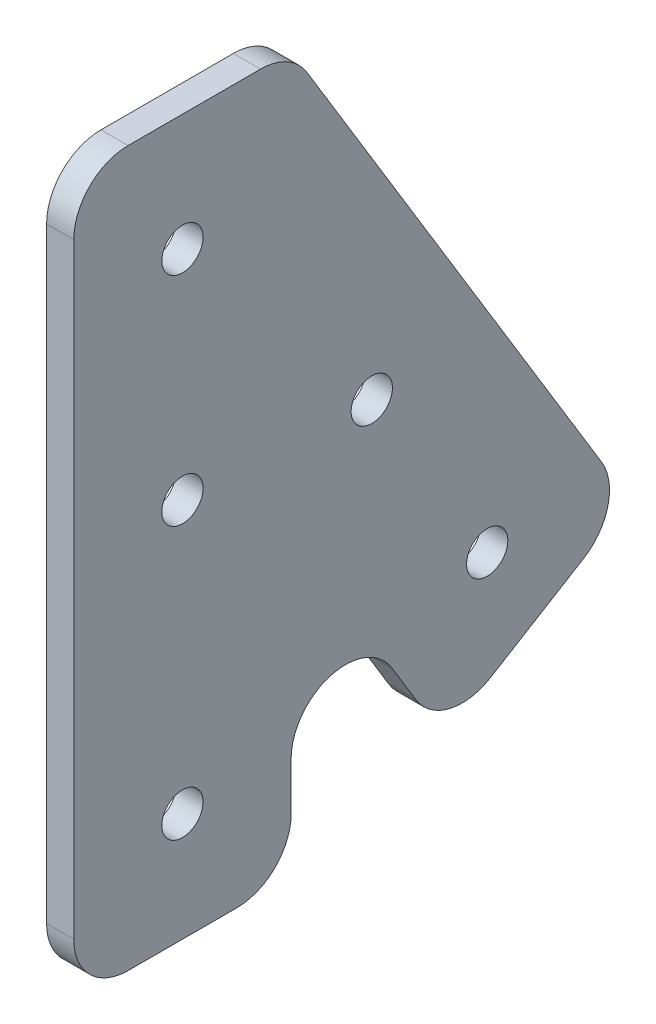
SolidWorks part; units mm, degrees
ref_plane "Front Plane" through (0, 0, 0) normal (0, 0, 1) x (1, 0, 0)
ref_plane "Top Plane" through (0, 0, 0) normal (0, 1, 0) x (1, 0, 0)
ref_plane "Right Plane" through (0, 0, 0) normal (1, 0, 0) x (0, 0, -1)
sketch "Sketch1" plane through (0, 0, 0) normal (1, 0, 0) x (0, 0, -1)
  line L0 (27.2549, 80.4378) -> (61.678, 23.7995)
  line L1 (6.35, 0) -> (19.05, 0)
  line L2 (0, 6.35) -> (0, 77.1398)
  line L3 (6.35, 83.4898) -> (21.8285, 83.4898)
  line L4 (25.4, 6.35) -> (25.4, 11.91)
  line L5 (59.5496, 15.0751) -> (48.6968, 8.4791)
  line L6 (39.9724, 10.6075) -> (37.1764, 15.208)
  arc A0 (39.9724, 10.6075) -> (48.6968, 8.4791) centre (45.3988, 13.9055) ccw
  arc A1 (59.5496, 15.0751) -> (61.678, 23.7995) centre (56.2516, 20.5015) ccw
  arc A2 (27.2549, 80.4378) -> (21.8285, 83.4898) centre (21.8285, 77.1398) ccw
  arc A3 (6.35, 83.4898) -> (0, 77.1398) centre (6.35, 77.1398) ccw
  arc A4 (6.35, 0) -> (0, 6.35) centre (6.35, 6.35) cw
  arc A5 (19.05, 0) -> (25.4, 6.35) centre (19.05, 6.35) ccw
  arc A6 (37.1764, 15.208) -> (25.4, 11.91) centre (31.75, 11.91) ccw
  point P10 (43.2704, 5.1811)
  point P13 (64.976, 18.3731)
  point P16 (25.4, 83.4898)
  point P19 (0, 83.4898)
  point P22 (0, 0)
  dimension "D7" = 6.35
  dimension "D1" = 25.4
  dimension "D2" = 83.4898
  dimension "D3" = 76.2
  dimension "D4" = 121.29
  dimension "D5" = 25.4
  dimension "D6" = 90
extrude "Boss-Extrude1" add sketch "Sketch1" along normal blind 3.175
sketch "Sketch2" plane through (3.175, 0, 0) normal (1, 0, 0) x (0, 0, -1)
  line L0 (6.35, 0) -> (19.05, 0) construction
  line L1 (61.678, 23.7995) -> (27.2549, 80.4378) construction
  circle A0 centre (12.7, 12.7) radius 2.413
  circle A1 centre (12.7, 44.45) radius 2.413
  circle A2 centre (12.7, 69.85) radius 2.413
  circle A3 centre (34.8216, 43.5352) radius 2.413
  circle A4 centre (48.3095, 21.3428) radius 2.413
  dimension "D1" = 4.826
  dimension "D2" = 12.7
  dimension "D3" = 4.826
  dimension "D4" = 31.75
  dimension "D5" = 4.826
  dimension "D6" = 25.4
  dimension "D7" = 4.826
  dimension "D8" = 12.7
  dimension "D9" = 4.826
  dimension "D10" = 12.7
extrude "Cut-Extrude1" cut sketch "Sketch2" against normal through all
